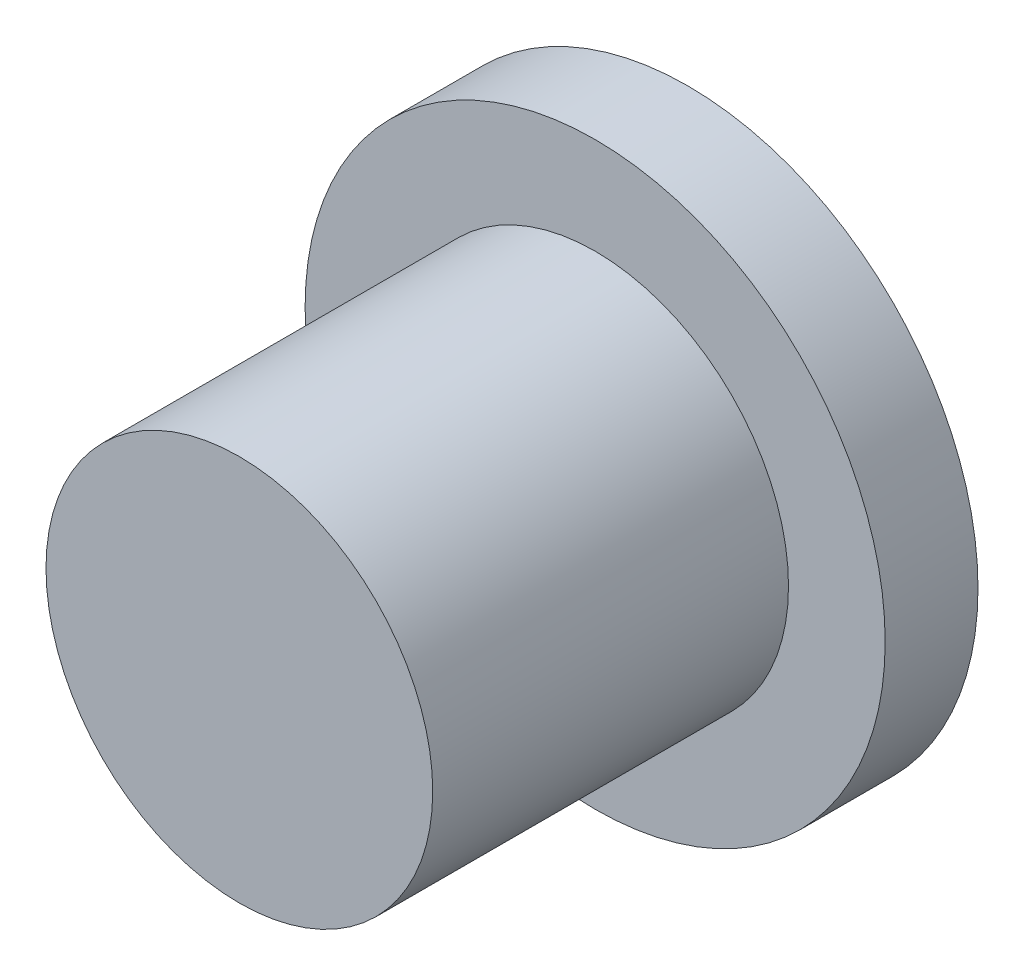
SolidWorks part; units mm, degrees
ref_plane "Front Plane" through (0, 0, 0) normal (0, 0, 1) x (1, 0, 0)
ref_plane "Top Plane" through (0, 0, 0) normal (0, 1, 0) x (1, 0, 0)
ref_plane "Right Plane" through (0, 0, 0) normal (1, 0, 0) x (0, 0, -1)
sketch "Sketch1" plane through (0, 0, 0) normal (0, 0, 1) x (1, 0, 0)
  circle A0 centre (0, 0) radius 2.5
extrude "M6 adjuster core" add sketch "Sketch1" along normal blind 5.8
sketch "Sketch2" plane through (0, 0, 0) normal (0, 0, 1) x (1, 0, 0)
  circle A0 centre (0, 0) radius 3.75
extrude "Jam nut envelope" add sketch "Sketch2" along normal blind 1.2
